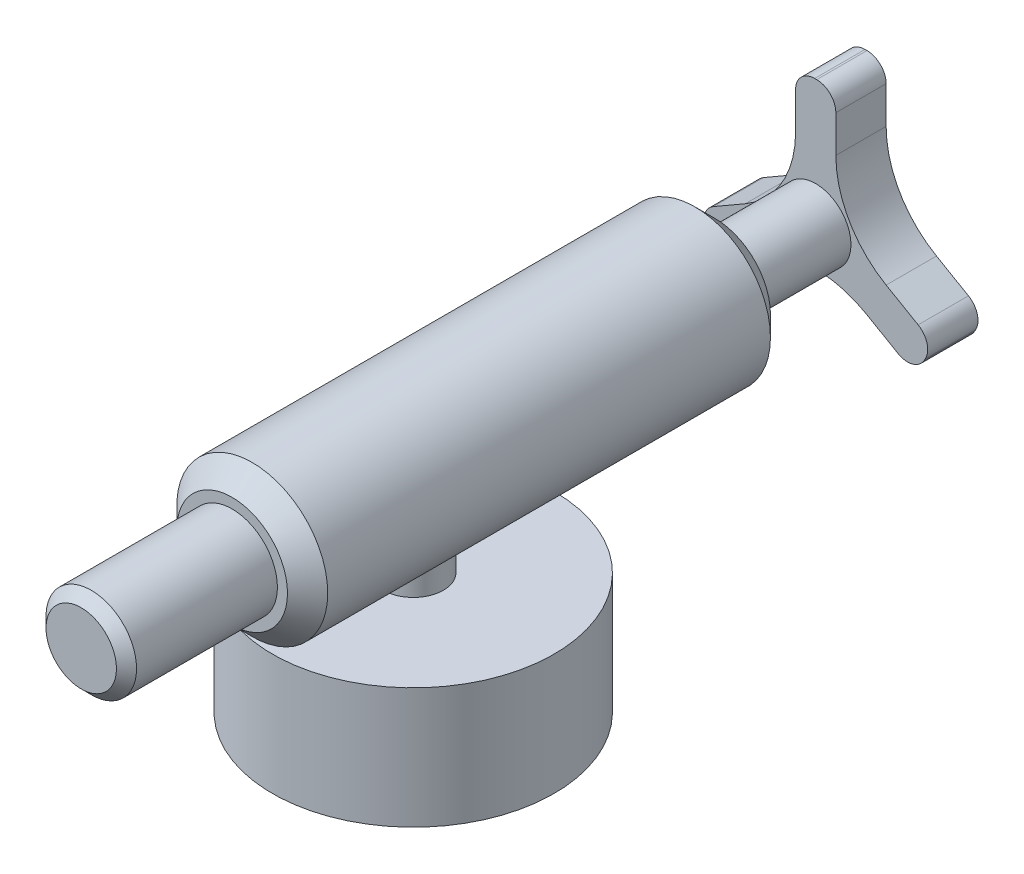
SolidWorks part; units mm, degrees
material "BUTYL"
ref_plane "Plan de face" through (0, 0, 0) normal (0, 0, 1) x (1, 0, 0)
ref_plane "Plan de dessus" through (0, 0, 0) normal (0, 1, 0) x (1, 0, 0)
ref_plane "Plan de droite" through (0, 0, 0) normal (1, 0, 0) x (0, 0, -1)
sketch "Esquisse1" plane through (0, 0, 0) normal (0, 0, 1) x (1, 0, 0)
  line L0 (0, 0) -> (0, 8.4412) construction
  line L1 (-12, 0) -> (-14, 0)
  line L2 (-14, 0) -> (-14, 12)
  line L3 (-14, 12) -> (-3, 12)
  line L4 (-3, 12) -> (-3, 18)
  line L5 (-3, 18) -> (0, 18)
  line L6 (-12, 0) -> (-12, 10)
  line L7 (-12, 10) -> (-10, 10)
  line L8 (0, 18) -> (0, 0)
  line L9 (-10, 10) -> (-10, 0)
  line L10 (-10, 0) -> (0, 0)
  dimension "D1" = 2
  dimension "D2" = 2
  dimension "D3" = 24
  dimension "D4" = 6
  dimension "D5" = 10
  dimension "D6" = 6
  dimension "D7" = 2
revolve "Révolution1" add sketch "Esquisse1" angle 360 about L0
sketch "Esquisse2" plane through (0, 0, 0) normal (0, 0, 1) x (1, 0, 0)
  line L0 (14, 12) -> (-14, 12) construction
  circle A0 centre (0, 22) radius 7.5
  dimension "D1" = 15
  dimension "D2" = 10
extrude "Boss.-Extru.1" add sketch "Esquisse2" against normal blind 30 and the other way blind 18
chamfer "Chanfrein1" distance 2 angle 45 2 edges at (7.5, 22, -30) (7.5, 22, 18)
sketch "Esquisse3" plane through (0, 0, 18) normal (0, 0, 1) x (1, 0, 0)
  circle A0 centre (0, 22) radius 4.5
  dimension "D1" = 9
extrude "Boss.-Extru.2" add sketch "Esquisse3" along normal blind 15
chamfer "Chanfrein2" distance 1 angle 45 1 edges at (4.5, 22, 33)
sketch "Esquisse4" plane through (0, 0, -30) normal (0, 0, -1) x (-1, 0, 0)
  circle A0 centre (0, 22) radius 3.5
  dimension "D1" = 7
extrude "Boss.-Extru.3" add sketch "Esquisse4" along normal blind 10
sketch "Esquisse5" plane through (0, 0, -40) normal (0, 0, -1) x (-1, 0, 0)
  line L0 (0, 25.5) -> (0, 35.6806) construction
  line L1 (-2, 28.9282) -> (-2, 32.6)
  line L2 (-0.1, 34.5) -> (0.1, 34.5)
  line L3 (2, 32.6) -> (2, 28.9282)
  line L4 (8.1799, 14.9679) -> (5, 16.8038)
  line L5 (10.8753, 15.8366) -> (10.7753, 15.6634)
  line L6 (7, 20.2679) -> (10.1799, 18.4321)
  line L7 (-10.1799, 18.4321) -> (-7, 20.2679)
  line L8 (-10.7753, 15.6634) -> (-10.8753, 15.8366)
  line L9 (-5, 16.8038) -> (-8.1799, 14.9679)
  circle A0 centre (0, 22) radius 3.5 construction
  arc A2 (-2, 28.9282) -> (-7, 20.2679) centre (-12, 28.9282) cw
  arc A3 (2, 28.9282) -> (7, 20.2679) centre (12, 28.9282) ccw
  arc A4 (5, 16.8038) -> (-5, 16.8038) centre (0, 8.1436) ccw
  arc A5 (2, 32.6) -> (0.1, 34.5) centre (0.1, 32.6) ccw
  arc A6 (-0.1, 34.5) -> (-2, 32.6) centre (-0.1, 32.6) ccw
  arc A7 (-10.8753, 15.8366) -> (-10.1799, 18.4321) centre (-9.2299, 16.7866) cw
  arc A8 (-10.7753, 15.6634) -> (-8.1799, 14.9679) centre (-9.1299, 16.6134) ccw
  arc A9 (10.7753, 15.6634) -> (8.1799, 14.9679) centre (9.1299, 16.6134) cw
  arc A10 (10.8753, 15.8366) -> (10.1799, 18.4321) centre (9.2299, 16.7866) ccw
  point P23 (0, 22)
  point P26 (2, 34.5)
  point P29 (-2, 34.5)
  dimension "D5" = 10
  dimension "D6" = 10
  dimension "D7" = 1.9
  dimension "D1" = 4
  dimension "D2" = 2
  dimension "D3" = 9
  dimension "D4" = 3
extrude "Boss.-Extru.4" add sketch "Esquisse5" along normal blind 5
